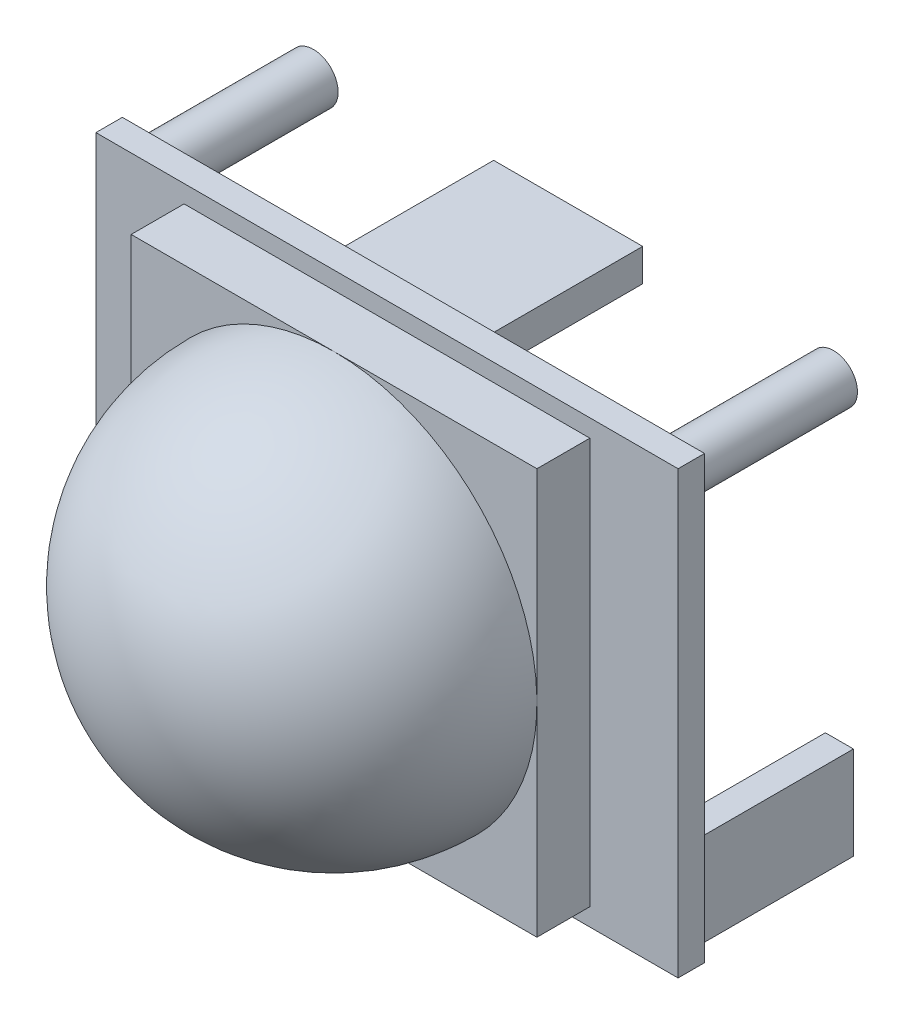
SolidWorks part; units mm, degrees
ref_plane "Спереди" through (0, 0, 0) normal (0, 0, 1) x (1, 0, 0)
ref_plane "Сверху" through (0, 0, 0) normal (0, 1, 0) x (1, 0, 0)
ref_plane "Справа" through (0, 0, 0) normal (1, 0, 0) x (0, 0, -1)
sketch "Эскиз1" plane through (0, 0, 0) normal (0, 0, 1) x (1, 0, 0)
  line L1 (-16.5, 12.5) -> (16.5, 12.5)
  line L2 (-16.5, 12.5) -> (-16.5, -12.5)
  line L3 (-16.5, -12.5) -> (16.5, -12.5)
  line L4 (16.5, 12.5) -> (16.5, -12.5)
  line L5 (-16.5, 12.5) -> (16.5, -12.5) construction
  line L6 (-16.5, -12.5) -> (16.5, 12.5) construction
  point P0 (0, 0)
  dimension "D1" = 33
  dimension "D2" = 25
extrude "Бобышка-Вытянуть1" add sketch "Эскиз1" along normal blind 10.5
sketch "Эскиз2" plane through (0, 0, 10.5) normal (0, 0, 1) x (1, 0, 0)
  line L1 (-11.5, 11.5) -> (11.5, 11.5)
  line L2 (-11.5, 11.5) -> (-11.5, -11.5)
  line L3 (-11.5, -11.5) -> (11.5, -11.5)
  line L4 (11.5, 11.5) -> (11.5, -11.5)
  line L5 (-11.5, 11.5) -> (11.5, -11.5) construction
  line L6 (-11.5, -11.5) -> (11.5, 11.5) construction
  point P0 (0, 0)
  dimension "D1" = 23
  dimension "D2" = 23
extrude "Бобышка-Вытянуть2" add sketch "Эскиз2" along normal blind 3
sketch "Эскиз3" plane through (0, 0, 0) normal (1, 0, 0) x (0, 0, -1)
  line L0 (2.7459, 0) -> (-26.7969, 0) construction
  line L1 (-25.0379, 0) -> (-13.5378, 0)
  line L2 (-13.5378, 0) -> (-13.5, 11.5)
  arc A0 (-13.5, 11.5) -> (-25.0379, 0) centre (-13.5378, 0) ccw
revolve "Повернуть1" add sketch "Эскиз3" angle 360 about L0
sketch "Эскиз4" plane through (0, 0, 0) normal (0, 0, -1) x (-1, 0, 0)
  line L1 (-3.9941, 11.9117) -> (4.4536, 11.9117)
  line L2 (-3.9941, 11.9117) -> (-3.9941, 10.0737)
  line L3 (-3.9941, 10.0737) -> (4.4536, 10.0737)
  line L4 (4.4536, 11.9117) -> (4.4536, 10.0737)
  line L5 (-15.9412, -6.7865) -> (-14.3506, -6.7865)
  line L6 (-15.9412, -6.7865) -> (-15.9412, -12.0531)
  line L7 (-15.9412, -12.0531) -> (-14.3506, -12.0531)
  line L8 (-14.3506, -6.7865) -> (-14.3506, -12.0531)
  line L9 (-5.408, -9.4198) -> (0.7069, -9.4198)
  line L10 (-5.408, -9.4198) -> (-5.408, -11.6643)
  line L11 (-5.408, -11.6643) -> (0.7069, -11.6643)
  line L12 (0.7069, -9.4198) -> (0.7069, -11.6643)
  line L13 (2.863, -9.4198) -> (8.5538, -9.4198)
  line L14 (2.863, -9.4198) -> (2.863, -11.6643)
  line L15 (2.863, -11.6643) -> (8.5538, -11.6643)
  line L16 (8.5538, -9.4198) -> (8.5538, -11.6643)
  line L17 (-16.5, 12.5) -> (16.5, 12.5)
  line L18 (-16.5, 12.5) -> (-16.5, -12.5)
  line L19 (-16.5, -12.5) -> (16.5, -12.5)
  line L20 (16.5, 12.5) -> (16.5, -12.5)
  circle A0 centre (-14.8101, 10.8513) radius 1.358
  circle A1 centre (14.6687, 10.8513) radius 1.3996
  circle A2 centre (-12.5833, -10.9927) radius 1.3338
  circle A3 centre (14.6687, -10.922) radius 1.3506
extrude "Вырез-Вытянуть1" cut sketch "Эскиз4" against normal blind 9
